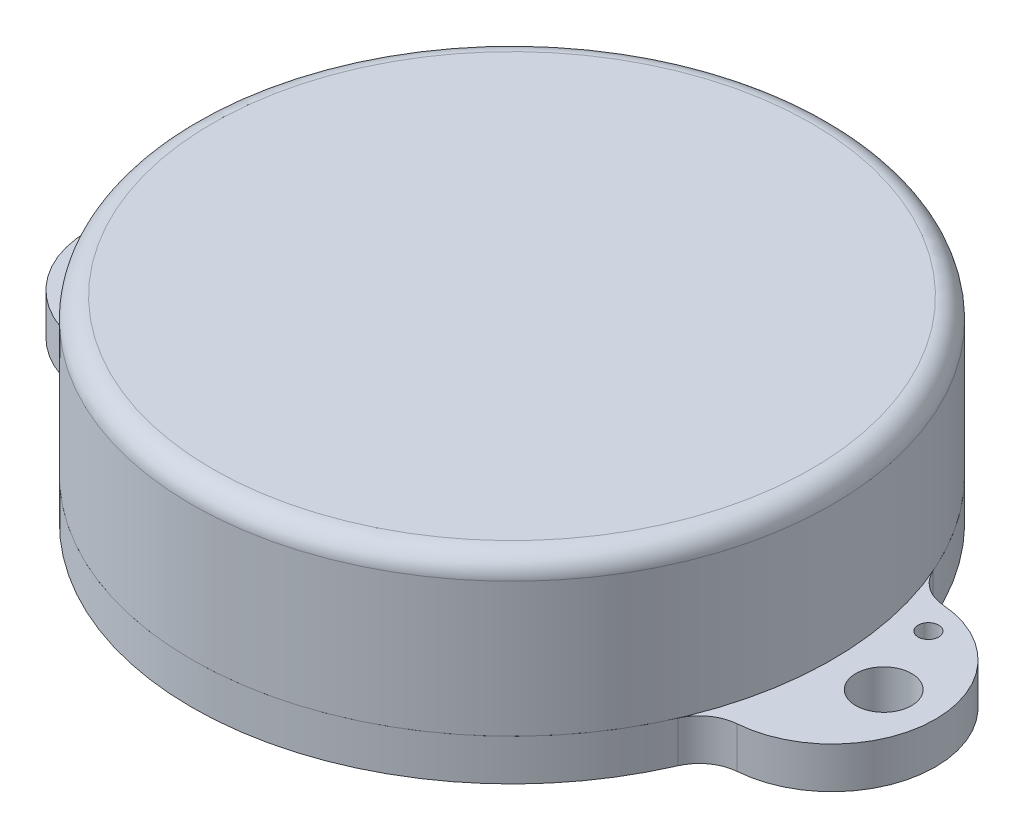
SolidWorks part; units mm, degrees
ref_plane "Front Plane" through (0, 0, 0) normal (0, 0, 1) x (1, 0, 0)
ref_plane "Top Plane" through (0, 0, 0) normal (0, 1, 0) x (1, 0, 0)
ref_plane "Right Plane" through (0, 0, 0) normal (1, 0, 0) x (0, 0, -1)
sketch "Sketch1" plane through (0, 0, 0) normal (0, 1, 0) x (1, 0, 0)
  line L0 (-16.6285, -3.5345) -> (16.6285, 3.5345) construction
  line L1 (0, 0) -> (10.8328, 0) construction
  arc A0 (-14.2143, -6.1809) -> (14.2143, -6.1809) centre (0, 0) ccw
  circle A1 centre (0, 0) radius 18 construction
  circle A2 centre (-18, 0) radius 1.35
  circle A3 centre (18, 0) radius 1.35
  circle A4 centre (0, 0) radius 17 construction
  circle A5 centre (16.6285, 3.5345) radius 0.5
  circle A6 centre (-16.6285, -3.5345) radius 0.5
  arc A7 (-15.8917, 4.9846) -> (-15.8917, -4.9846) centre (-15.5, 0) ccw
  arc A8 (-15.8917, -4.9846) -> (-14.2143, -6.1809) centre (-16.0484, -6.9785) cw
  arc A9 (-15.8917, 4.9846) -> (-14.2143, 6.1809) centre (-16.0484, 6.9785) ccw
  arc A10 (15.8917, -4.9846) -> (15.8917, 4.9846) centre (15.5, 0) ccw
  arc A11 (14.2143, 6.1809) -> (-14.2143, 6.1809) centre (0, 0) ccw
  arc A12 (15.8917, -4.9846) -> (14.2143, -6.1809) centre (16.0484, -6.9785) ccw
  arc A13 (15.8917, 4.9846) -> (14.2143, 6.1809) centre (16.0484, 6.9785) cw
  point P27 (14.6935, 4.9345)
  dimension "D1" = 31
  dimension "D2" = 36
  dimension "D3" = 2.7
  dimension "D4" = 34
  dimension "D6" = 1
  dimension "D7" = 10
  dimension "D8" = 2
  dimension "D9" = 10
  dimension "D10" = 2
  dimension "D5" = 12
extrude "Boss-Extrude1" add sketch "Sketch1" along normal blind 2
sketch "Sketch2" plane through (0, 2, 0) normal (0, 1, 0) x (1, 0, 0)
  circle A4 centre (0, 0) radius 15.5
extrude "Boss-Extrude2" add sketch "Sketch2" along normal blind 7.5 separate body
sketch "Sketch3" plane through (0, 0, 0) normal (0, 0, 1) x (1, 0, 0)
  line L1 (-4.0222, 8.6629) -> (4.0222, 8.6629)
  line L2 (-4.0222, 8.6629) -> (-4.0222, 5.69)
  line L3 (-4.0222, 5.69) -> (4.0222, 5.69)
  line L4 (4.0222, 8.6629) -> (4.0222, 5.69)
  line L5 (-4.0222, 8.6629) -> (4.0222, 5.69) construction
  line L6 (-4.0222, 5.69) -> (4.0222, 8.6629) construction
  point P0 (0, 7.1765)
fillet "Fillet1" radius 1 1 edges at (0, 9.5, 15.5)
